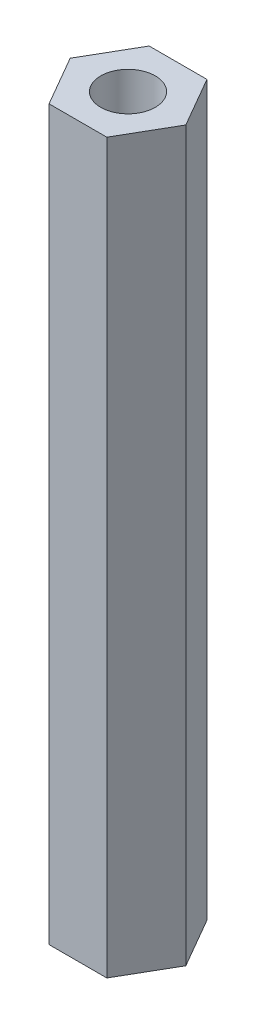
SolidWorks part; units mm, degrees
material "黄铜"
ref_plane "前视基准面" through (0, 0, 0) normal (0, 0, 1) x (1, 0, 0)
ref_plane "上视基准面" through (0, 0, 0) normal (0, 1, 0) x (1, 0, 0)
ref_plane "右视基准面" through (0, 0, 0) normal (1, 0, 0) x (0, 0, -1)
other "Configuration Table"
sketch "草图1" plane through (0, 0, 0) normal (0, 1, 0) x (1, 0, 0)
  line L1 (3.1754, 0) -> (1.5877, 2.75)
  line L2 (1.5877, 2.75) -> (-1.5877, 2.75)
  line L3 (-1.5877, 2.75) -> (-3.1754, 0)
  line L4 (-3.1754, 0) -> (-1.5877, -2.75)
  line L5 (-1.5877, -2.75) -> (1.5877, -2.75)
  line L6 (1.5877, -2.75) -> (3.1754, 0)
  circle A0 centre (0, 0) radius 2.75 construction
  circle A1 centre (0, 0) radius 1.5
  dimension "D1" = 5.5
  dimension "D2" = 3
extrude "凸台-拉伸1" add sketch "草图1" along normal blind 40
